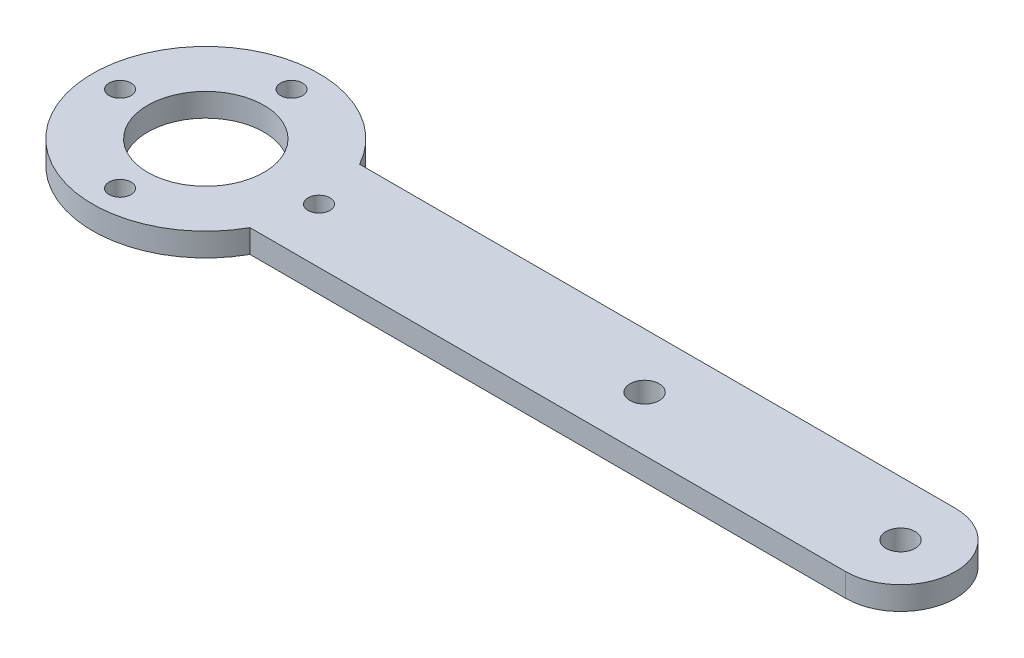
SolidWorks part; units mm, degrees
ref_plane "Front Plane" through (0, 0, 0) normal (0, 0, 1) x (1, 0, 0)
ref_plane "Top Plane" through (0, 0, 0) normal (0, 1, 0) x (1, 0, 0)
ref_plane "Right Plane" through (0, 0, 0) normal (1, 0, 0) x (0, 0, -1)
sketch "Sketch1" plane through (0, 0, 0) normal (0, 1, 0) x (1, 0, 0)
  line L0 (0, 0) -> (95, 0) construction
  line L1 (13.5361, 7.5) -> (95, 7.5)
  line L3 (95, -7.5) -> (13.5361, -7.5)
  line L4 (95, 0) -> (102.5, 0) construction
  line L7 (95, 7.5) -> (95, -7.5) construction
  arc A0 (13.5361, 7.5) -> (13.5361, -7.5) centre (0, 0) ccw
  circle A1 centre (0, 0) radius 7.95
  arc A2 (13.5361, -7.5) -> (13.5361, 7.5) centre (0, 0) ccw construction
  circle A5 centre (0, 0) radius 11.725 construction
  circle A6 centre (0, -11.725) radius 1.5
  circle A7 centre (0, 11.725) radius 1.5
  arc A8 (95, -7.5) -> (95, 7.5) centre (95, 0) ccw
  circle A9 centre (-11.725, 0) radius 1.5
  circle A10 centre (15.475, 0) radius 1.5
  circle A11 centre (95, 0) radius 2
  circle A12 centre (60, 0) radius 2
  dimension "D1" = 15.9
  dimension "D2" = 30.95
  dimension "D5" = 35
  dimension "D8" = 7.525
  dimension "D9" = 23.45
  dimension "D10" = 3
  dimension "D6" = 4
  dimension "D3" = 15
  dimension "D4" = 95
extrude "Boss-Extrude1" add sketch "Sketch1" along normal blind 3.175
